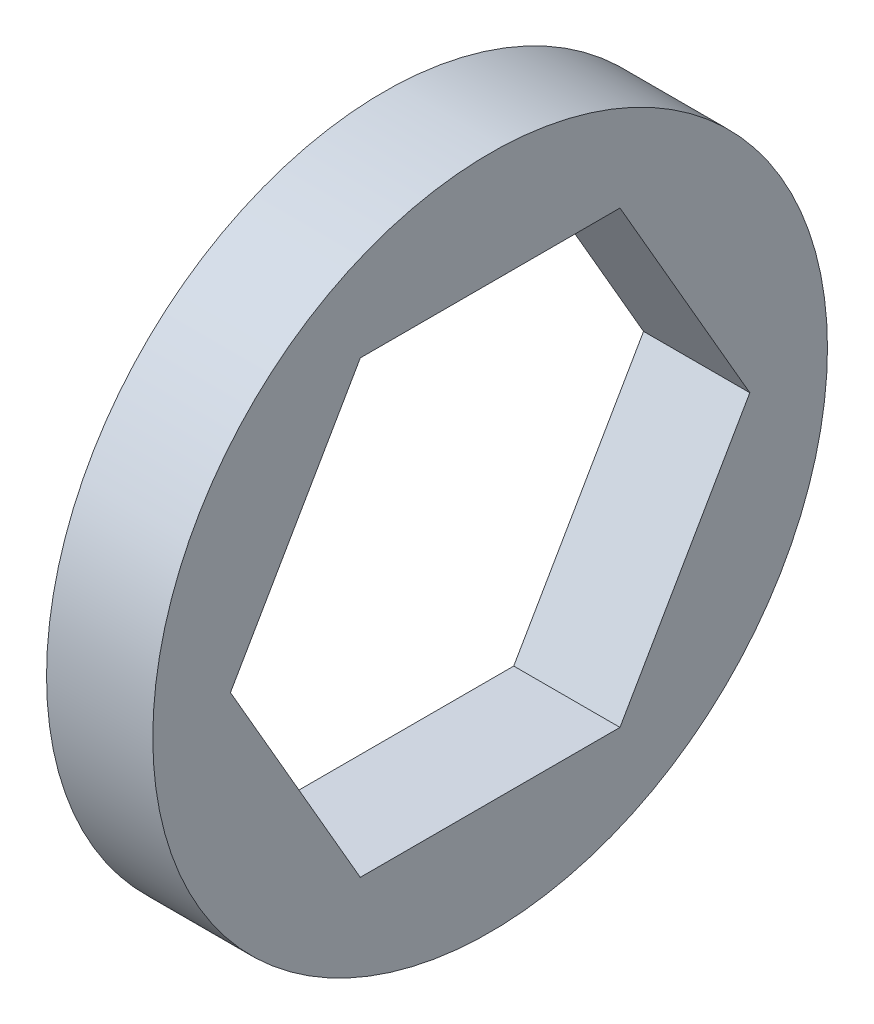
SolidWorks part; units mm, degrees
material "POM Acetal Copolymer"
ref_plane "Front Plane" through (0, 0, 0) normal (0, 0, 1) x (1, 0, 0)
ref_plane "Top Plane" through (0, 0, 0) normal (0, 1, 0) x (1, 0, 0)
ref_plane "Right Plane" through (0, 0, 0) normal (1, 0, 0) x (0, 0, -1)
sketch "Sketch1" plane through (0, 0, 0) normal (1, 0, 0) x (0, 0, -1)
  line L1 (7.3323, 0) -> (3.6662, 6.35)
  line L2 (3.6662, 6.35) -> (-3.6662, 6.35)
  line L3 (-3.6662, 6.35) -> (-7.3323, 0)
  line L4 (-7.3323, 0) -> (-3.6662, -6.35)
  line L5 (-3.6662, -6.35) -> (3.6662, -6.35)
  line L6 (3.6662, -6.35) -> (7.3323, 0)
  circle A0 centre (0, 0) radius 6.35 construction
  circle A1 centre (0, 0) radius 9.525
  dimension "D1" = 12.7
  dimension "D2" = 3.175
extrude "Boss-Extrude1" add sketch "Sketch1" along normal mid plane 3
